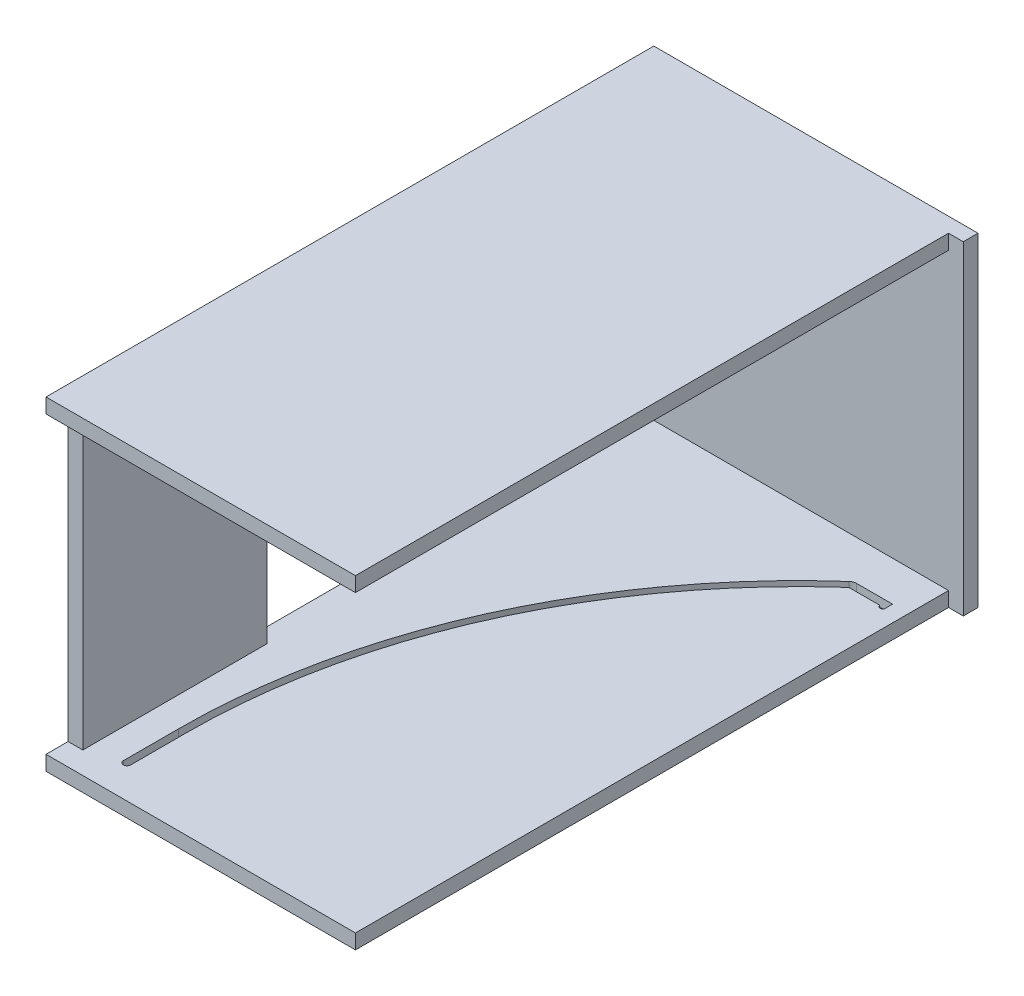
SolidWorks part; units mm, degrees
ref_plane "Front Plane" through (0, 0, 0) normal (0, 0, 1) x (1, 0, 0)
ref_plane "Top Plane" through (0, 0, 0) normal (0, 1, 0) x (1, 0, 0)
ref_plane "Right Plane" through (0, 0, 0) normal (1, 0, 0) x (0, 0, -1)
sketch "Sketch1" plane through (0, 0, 0) normal (0, 0, 1) x (1, 0, 0)
  line L1 (-220, 220) -> (220, 220)
  line L2 (-220, 220) -> (-220, -220)
  line L3 (-220, -220) -> (220, -220)
  line L4 (220, 220) -> (220, -220)
  line L5 (-220, 220) -> (220, -220) construction
  line L6 (-220, -220) -> (220, 220) construction
  point P0 (0, 0)
  dimension "D1" = 440
  dimension "D2" = 440
extrude "Boss-Extrude1" add sketch "Sketch1" along normal blind 20
sketch "Sketch2" plane through (0, 0, 20) normal (0, 0, 1) x (1, 0, 0)
  line L1 (-220, -220) -> (200, -220)
  line L2 (-220, -220) -> (-220, -200)
  line L3 (-220, -200) -> (200, -200)
  line L4 (200, -220) -> (200, -200)
  dimension "D1" = 20
  dimension "D2" = 420
extrude "Boss-Extrude2" add sketch "Sketch2" along normal blind 805
sketch "Sketch3" plane through (0, -200, 0) normal (0, 1, 0) x (1, 0, 0)
  line L1 (-220, -20) -> (-200, -20)
  line L2 (-220, -20) -> (-220, -270)
  line L3 (-220, -270) -> (-200, -270)
  line L4 (-200, -20) -> (-200, -270)
  dimension "D1" = 20
  dimension "D2" = 250
extrude "Boss-Extrude3" add sketch "Sketch3" along normal blind 400
sketch "Sketch4" plane through (0, -200, 0) normal (0, 1, 0) x (1, 0, 0)
  line L0 (-220, -825) -> (-220, -270) construction
  line L1 (-220, -795) -> (-200, -795)
  line L2 (-220, -795) -> (-220, -545)
  line L3 (-220, -545) -> (-200, -545)
  line L4 (-200, -795) -> (-200, -545)
  line L5 (200, -825) -> (-220, -825) construction
  dimension "D1" = 20
  dimension "D2" = 30
  dimension "D3" = 250
extrude "Boss-Extrude4" add sketch "Sketch4" along normal blind 400
sketch "Sketch5" plane through (0, -200, 0) normal (0, 1, 0) x (1, 0, 0)
  line L0 (178, -74) -> (178, -84)
  line L1 (178, -74) -> (129.1707, -74)
  line L2 (200, -825) -> (200, -20) construction
  line L3 (131.0769, -84) -> (169.3765, -84)
  line L4 (200, -20) -> (-200, -20) construction
  line L5 (-160, -705) -> (-160, -780)
  line L6 (200, -825) -> (-220, -825) construction
  line L7 (-220, -825) -> (-220, -795) construction
  line L8 (-150, -705) -> (-150, -780)
  line L9 (119.5229, -92.3667) -> (119.5229, -92.3667)
  line L10 (119.5229, -92.3667) -> (119.5229, -92.3667)
  line L11 (119.5229, -92.3667) -> (119.5229, -92.3667)
  line L12 (125, -84) -> (169.3765, -84) construction
  arc A0 (171.2396, -85.2727) -> (178, -84) centre (174.5, -84) ccw
  arc A1 (169.3765, -84) -> (171.2396, -85.2727) centre (169.3765, -86) cw
  arc A2 (-160, -705) -> (121.8571, -76.7834) centre (681.0281, -705) cw
  arc A3 (129.1707, -74) -> (121.8571, -76.7834) centre (129.1707, -85) ccw
  arc A4 (-150, -705) -> (127.0774, -85.5274) centre (681.0281, -705) cw
  arc A5 (119.5229, -92.3667) -> (119.5229, -92.3667) centre (119.5229, -92.3667) ccw
  arc A6 (119.5229, -92.3667) -> (119.5229, -92.3667) centre (119.5229, -92.3667) ccw
  arc A7 (119.5229, -92.3667) -> (119.5229, -92.3667) centre (119.5229, -92.3667) ccw
  arc A8 (-160, -780) -> (-150, -780) centre (-155, -780) ccw
  arc A9 (-150, -705) -> (119.5229, -92.3667) centre (681.0281, -705) cw construction
  arc A10 (127.0774, -85.5274) -> (131.0769, -84) centre (131.0769, -90) cw
  point P5 (178, -79)
  point P11 (171, -84)
  point P20 (-160, -705)
  point P24 (125, -74)
  dimension "D5" = 7
  dimension "D4" = 2
  dimension "D10" = 10
  dimension "D7" = 11
  dimension "D11" = 6
  dimension "D1" = 10
  dimension "D2" = 53
  dimension "D3" = 22
  dimension "D6" = 54
  dimension "D8" = 45
  dimension "D9" = 60
extrude "Cut-Extrude1" cut sketch "Sketch5" against normal blind 12 contours A4 A10 L3 A1 A0 L0 L1 A3 A2 L5 A8 L8
mirror "Mirror1" about plane through (0, 0, 0) normal (0, 1, 0) of "Cut-Extrude1", "Boss-Extrude2"
sketch "Sketch6" plane through (0, -212, 0) normal (0, 1, 0) x (1, 0, 0)
  line L0 (-155, -755) -> (-155, -705)
  line L1 (131.0769, -79) -> (169.3765, -79)
  arc A0 (123.7444, -81.8003) -> (-155, -705) centre (681.0281, -705) ccw
  arc A1 (131.0769, -79) -> (123.7444, -81.8003) centre (131.0769, -90) ccw
